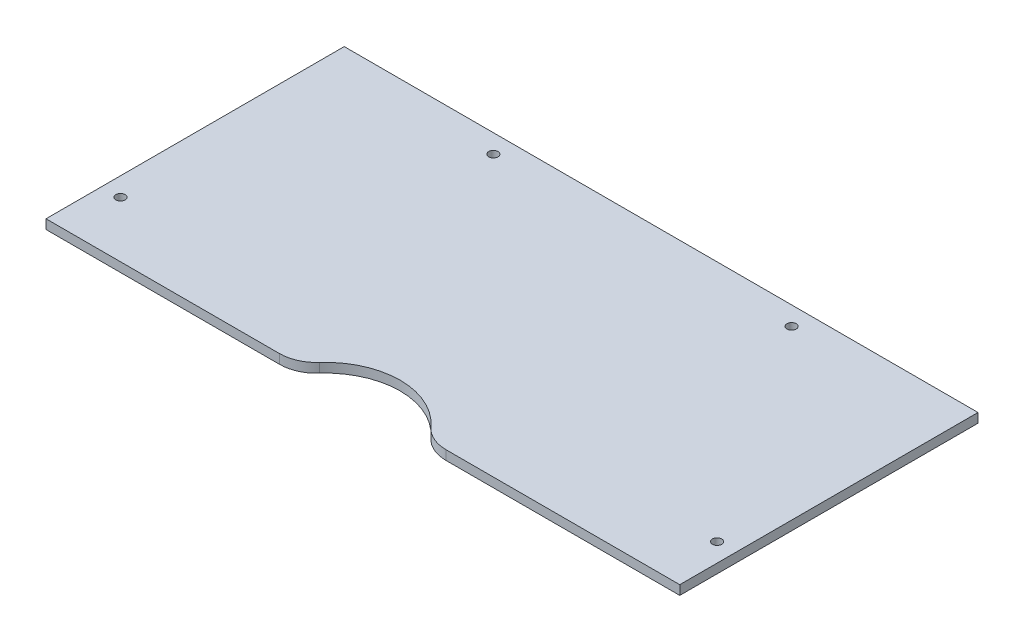
SolidWorks part; units mm, degrees
material "Zoltek Panex 33"
ref_plane "Front Plane" through (0, 0, 0) normal (0, 0, 1) x (1, 0, 0)
ref_plane "Top Plane" through (0, 0, 0) normal (0, 1, 0) x (1, 0, 0)
ref_plane "Right Plane" through (0, 0, 0) normal (1, 0, 0) x (0, 0, -1)
sketch "Sketch1" plane through (0, 0, 0) normal (0, 1, 0) x (1, 0, 0)
  line L0 (0, 101.6) -> (0, 0)
  line L1 (0, 0) -> (215.9, 0)
  line L2 (0, 0) -> (0, 228.6)
  line L3 (0, 228.6) -> (215.9, 228.6)
  line L4 (215.9, 0) -> (215.9, 228.6)
  line L5 (0, 127) -> (85.953, 127)
  line L6 (0, 127) -> (0, 101.6)
  line L7 (0, 101.6) -> (85.953, 101.6)
  line L8 (85.953, 127) -> (85.953, 101.6)
  line L9 (215.9, 127) -> (129.947, 127)
  line L10 (215.9, 127) -> (215.9, 101.6)
  line L11 (215.9, 101.6) -> (129.947, 101.6)
  line L12 (129.947, 127) -> (129.947, 101.6)
  line L13 (215.9, 0) -> (215.9, 101.6)
  circle A0 centre (107.95, 114.3) radius 25.4
  point P13 (85.953, 114.3)
  point P18 (0, 114.3)
  dimension "D4" = 50.8
  dimension "D5" = 85.953
  dimension "D1" = 228.6
  dimension "D2" = 215.9
  dimension "D3" = 25.4
extrude "Boss-Extrude1" add sketch "Sketch1" along normal blind 3.175 contours A0 L9 L4 L3 L2 L5
fillet "Fillet1" radius 12.7 2 edges at (129.947, 1.5875, -127) (85.953, 1.5875, -127)
sketch "Sketch2" plane through (0, 3.175, 0) normal (0, 1, 0) x (1, 0, 0)
  line L0 (0, 127) -> (0, 228.6) construction
  line L1 (0, 228.6) -> (215.9, 228.6) construction
  line L2 (215.9, 127) -> (215.9, 228.6) construction
  line L3 (0, 127) -> (79.5519, 127) construction
  line L4 (215.9, 127) -> (136.3481, 127) construction
  circle A0 centre (6.35, 146.05) radius 1.5875
  circle A1 centre (57.15, 222.25) radius 1.5875
  circle A2 centre (158.75, 222.25) radius 1.5875
  circle A3 centre (209.55, 146.05) radius 1.5875
  dimension "D1" = 3.175
  dimension "D2" = 6.35
  dimension "D3" = 6.35
  dimension "D4" = 6.35
  dimension "D5" = 6.35
  dimension "D6" = 57.15
  dimension "D7" = 19.05
  dimension "D8" = 57.15
  dimension "D9" = 19.05
extrude "Cut-Extrude1" cut sketch "Sketch2" against normal through all
